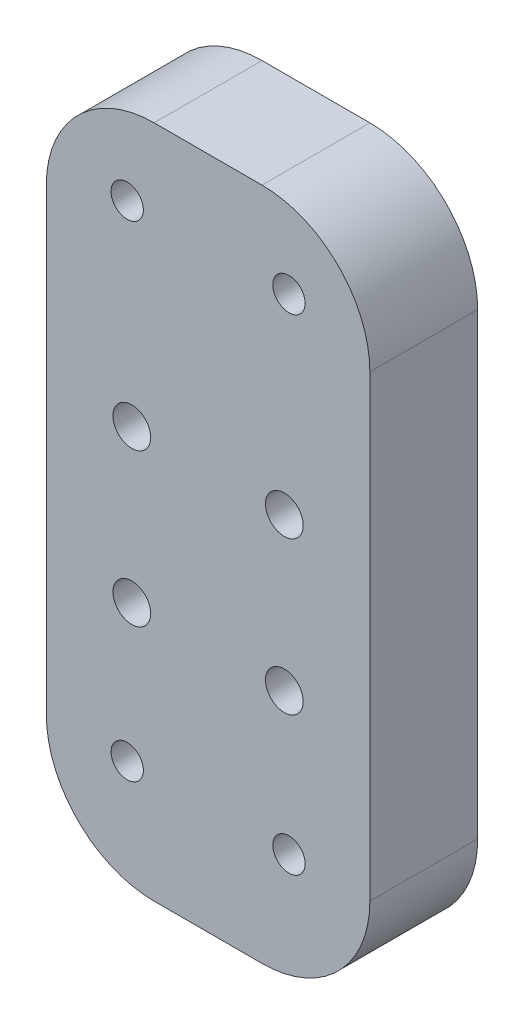
SolidWorks part; units mm, degrees
ref_plane "前视基准面" through (0, 0, 0) normal (0, 0, 1) x (1, 0, 0)
ref_plane "上视基准面" through (0, 0, 0) normal (0, 1, 0) x (1, 0, 0)
ref_plane "右视基准面" through (0, 0, 0) normal (1, 0, 0) x (0, 0, -1)
sketch "草图1" plane through (0, 0, 0) normal (0, 0, 1) x (1, 0, 0)
  line L1 (-15, 32.5) -> (15, 32.5)
  line L2 (-15, 32.5) -> (-15, -30)
  line L3 (-15, -30) -> (15, -30)
  line L4 (15, 32.5) -> (15, -30)
  line L12 (-7.0711, -7.0711) -> (7.0711, 7.0711) construction
  line L13 (-7.0711, 7.0711) -> (7.0711, -7.0711) construction
  circle A1 centre (7.0711, 7.0711) radius 1.75
  circle A2 centre (-7.0711, 7.0711) radius 1.75
  circle A3 centre (7.0711, -7.0711) radius 1.75
  circle A4 centre (-7.0711, -7.0711) radius 1.75
  circle A5 centre (7.5, 25) radius 1.5
  circle A6 centre (-7.5, 25) radius 1.5
  circle A7 centre (7.5, -20) radius 1.5
  circle A8 centre (-7.5, -20) radius 1.5
  point P1 (0, 0)
extrude "凸台-拉伸1" add sketch "草图1" along normal blind 10
fillet "圆角1" radius 10 4 edges at (-15, -30, 5) (15, -30, 5) (-15, 32.5, 5) (15, 32.5, 5)
